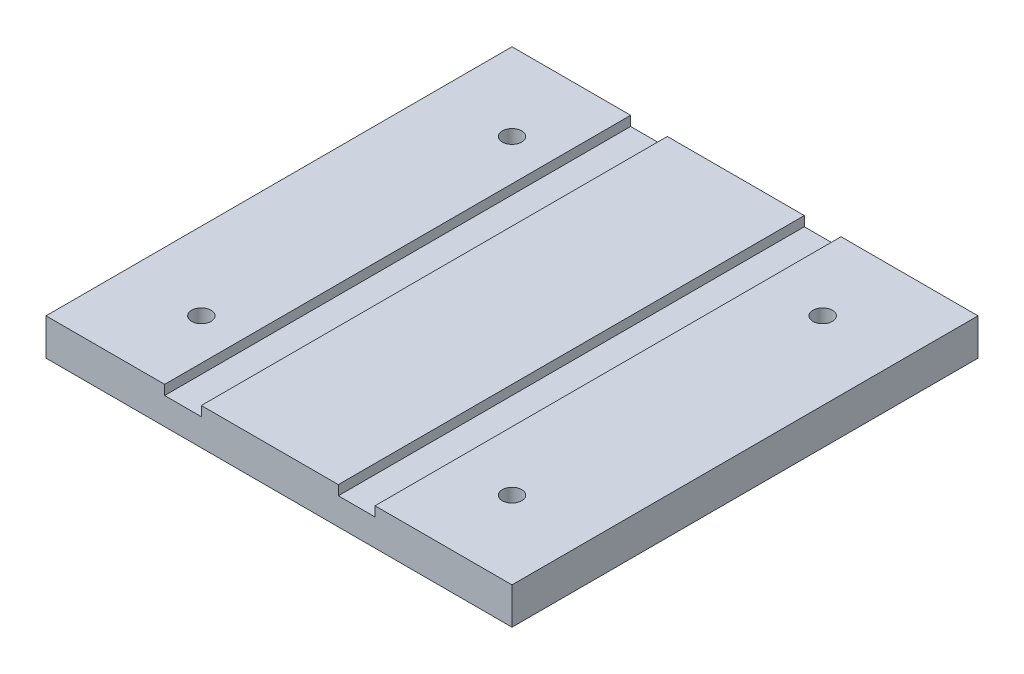
SolidWorks part; units mm, degrees
ref_plane "Front Plane" through (0, 0, 0) normal (0, 0, 1) x (1, 0, 0)
ref_plane "Top Plane" through (0, 0, 0) normal (0, 1, 0) x (1, 0, 0)
ref_plane "Right Plane" through (0, 0, 0) normal (1, 0, 0) x (0, 0, -1)
sketch "Sketch1" plane through (0, 0, 0) normal (0, 1, 0) x (1, 0, 0)
  line L1 (-76.2, 76.2) -> (76.2, 76.2)
  line L2 (-76.2, 76.2) -> (-76.2, -76.2)
  line L3 (-76.2, -76.2) -> (76.2, -76.2)
  line L4 (76.2, 76.2) -> (76.2, -76.2)
  line L5 (-76.2, 76.2) -> (76.2, -76.2) construction
  line L6 (-76.2, -76.2) -> (76.2, 76.2) construction
  circle A0 centre (-50.8, 50.8) radius 3.175
  circle A1 centre (50.8, 50.8) radius 3.175
  circle A2 centre (-50.8, -50.8) radius 3.175
  circle A3 centre (50.8, -50.8) radius 3.175
  point P0 (0, 0)
  dimension "D3" = 6.35
  dimension "D4" = 6.35
  dimension "D5" = 6.35
  dimension "D6" = 6.35
  dimension "D7" = 25.4
  dimension "D8" = 25.4
  dimension "D9" = 25.4
  dimension "D10" = 101.6
  dimension "D11" = 25.4
  dimension "D12" = 25.4
  dimension "D13" = 25.4
  dimension "D14" = 25.4
  dimension "D15" = 76.2
  dimension "D1" = 152.4
  dimension "D2" = 152.4
  dimension "D16" = 76.2
extrude "Boss-Extrude1" add sketch "Sketch1" along normal blind 12
sketch "Sketch2" plane through (0, 12, 0) normal (0, 1, 0) x (1, 0, 0)
  line L0 (-76.2, 76.2) -> (-76.2, -76.2) construction
  line L1 (-25.4, -76.2) -> (-37.4, -76.2)
  line L2 (-25.4, -76.2) -> (-25.4, 76.2)
  line L3 (-25.4, 76.2) -> (-37.4, 76.2)
  line L4 (-37.4, -76.2) -> (-37.4, 76.2)
  line L5 (-25.4, -76.2) -> (-37.4, 76.2) construction
  line L6 (-25.4, 76.2) -> (-37.4, -76.2) construction
  line L7 (-76.2, -76.2) -> (76.2, -76.2) construction
  line L8 (76.2, -76.2) -> (76.2, 76.2) construction
  line L9 (31.4, -76.2) -> (19.4, -76.2)
  line L10 (31.4, -76.2) -> (31.4, 76.2)
  line L11 (31.4, 76.2) -> (19.4, 76.2)
  line L12 (19.4, -76.2) -> (19.4, 76.2)
  line L13 (31.4, -76.2) -> (19.4, 76.2) construction
  line L14 (31.4, 76.2) -> (19.4, -76.2) construction
  point P0 (-31.4, 0)
  point P9 (25.4, 0)
  dimension "D1" = 44.8
  dimension "D2" = 12
  dimension "D3" = 152.4
  dimension "D4" = 0
  dimension "D5" = 0
  dimension "D6" = 152.4
  dimension "D7" = 12
  dimension "D8" = 44.8
extrude "Cut-Extrude1" cut sketch "Sketch2" against normal blind 3.175
